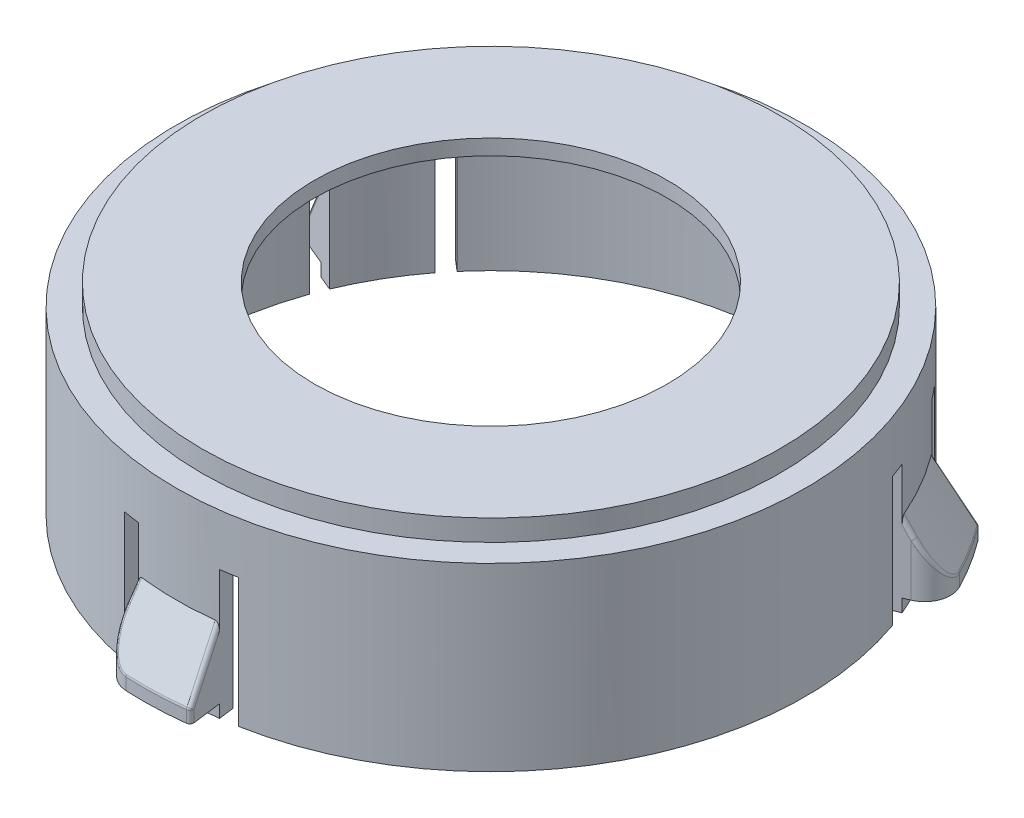
SolidWorks part; units mm, degrees
ref_plane "Front Plane" through (0, 0, 0) normal (0, 0, 1) x (1, 0, 0)
ref_plane "Top Plane" through (0, 0, 0) normal (0, 1, 0) x (1, 0, 0)
ref_plane "Right Plane" through (0, 0, 0) normal (1, 0, 0) x (0, 0, -1)
sketch "Sketch1" plane through (0, 0, 0) normal (0, 1, 0) x (1, 0, 0)
  circle A0 centre (0, 0) radius 24.5
  dimension "D1" = 49
extrude "Boss-Extrude1" add sketch "Sketch1" along normal blind 15.7
sketch "Sketch2" plane through (0, 15.7, 0) normal (0, 1, 0) x (1, 0, 0)
  circle A0 centre (0, 0) radius 22.5
  circle A1 centre (0, 0) radius 24.5 construction
  circle A2 centre (0, 0) radius 24.5
  dimension "D1" = 45
extrude "Cut-Extrude1" cut sketch "Sketch2" against normal blind 1.65
sketch "Sketch3" plane through (0, 15.7, 0) normal (0, 1, 0) x (1, 0, 0)
  circle A0 centre (0, 0) radius 13.75
  dimension "D1" = 27.5
shell "Shell1" thickness 1.2
extrude "Cut-Extrude2" cut sketch "Sketch3" against normal up to surface (1.2 mm away) up to face at (0, 14.5, 21.3)
sketch "Sketch4" plane through (0, 0, 0) normal (1, 0, 0) x (0, 0, -1)
  line L0 (-24.5, 6.5) -> (-24.5, 1)
  line L1 (-24.5, 14.05) -> (-24.5, 0) construction
  line L2 (-24.5, 14.05) -> (-24.5, 0) construction
  line L3 (-24.5, 1) -> (-27.1, 1)
  line L4 (-27.1, 1) -> (-27.1, 2)
  line L5 (-27.1, 2) -> (-24.5, 6.5)
  dimension "D1" = 2.6
  dimension "D2" = 1
  dimension "D3" = 5.5
  dimension "D4" = 1
ref_plane "Plane1" through (0, 1, 24.5) normal (0, -1, 0) x (-1, 0, 0)
sketch "Sketch5" plane through (0, 1, 24.5) normal (0, -1, 0) x (-1, 0, 0)
  line L0 (0, 0) -> (0, -8.4757) construction
  line L1 (0, 0) -> (0, -2.6) construction
  line L2 (0, -2.6) -> (-6.262, -2.6) construction
  line L3 (-3.5, -2.373) -> (-3.5, -2.6) construction
  line L4 (3.5, -2.373) -> (3.5, -2.6) construction
  circle A2 centre (0, 24.5) radius 27.1
  arc A3 (-3.5, -2.373) -> (3.5, -2.373) centre (0, 24.5) ccw
  point P15 (0, -2.6)
  dimension "D2" = 3.5
  dimension "D3" = 3.5
  dimension "D1" = 2.6
sweep "Sweep1" add profiles "Sketch4" path "Sketch5"
fillet "Fillet2" radius 2 1 edges at (-3.5, 1.5, 26.873)
fillet "Fillet3" radius 0.3 5 edges at (-3.1978, 6.0498, 24.5527) (1.0805, 2, 27.0784) (3.5, 1.5, 26.873) (3.3321, 4.25, 25.5839) (-2.2759, 2.3787, 26.7847)
sketch "Sketch7" plane through (0, 0, 0) normal (0, -1, 0) x (1, 0, 0)
  line L0 (3.461, 26.5739) -> (3.1642, 24.2948) construction
  line L1 (-3.2314, 24.8106) -> (-3.1642, 24.2948) construction
  line L2 (3.461, 26.5739) -> (3.1642, 24.2948) construction
  line L3 (-3.2314, 24.8106) -> (-3.1642, 24.2948) construction
  line L4 (0, 0) -> (7.9298, 43.1191) construction
  line L5 (0, 0) -> (-8.9475, 48.653) construction
  line L6 (-3.1642, 24.2948) -> (-3.0092, 23.1049)
  line L7 (-4.4314, 24.0959) -> (-4.2143, 22.9157)
  line L8 (3.1642, 24.2948) -> (3.0092, 23.1049)
  line L9 (4.4314, 24.0959) -> (4.2143, 22.9157)
  circle A0 centre (0, 0) radius 23.3 construction
  circle A1 centre (0, 0) radius 24.5 construction
  arc A2 (-3.0092, -23.1049) -> (3.0092, -23.1049) centre (0, 0) ccw
  arc A3 (-3.1642, -24.2948) -> (3.1642, -24.2948) centre (0, 0) ccw
  arc A4 (4.4314, 24.0959) -> (3.1642, 24.2948) centre (0, 0) ccw
  arc A5 (4.2143, 22.9157) -> (3.0092, 23.1049) centre (0, 0) ccw
  arc A6 (-3.0092, 23.1049) -> (-4.2143, 22.9157) centre (0, 0) ccw
  arc A7 (-3.1642, 24.2948) -> (-4.4314, 24.0959) centre (0, 0) ccw
  point P18 (4.4314, 24.0959)
  point P19 (4.2143, 22.9157)
  point P20 (-4.2143, 22.9157)
  point P21 (-4.4314, 24.0959)
  circle M5 centre (0, 0) radius 23.3
  circle M6 centre (0, 0) radius 24.5
  dimension "D1" = 3
  dimension "D2" = 3
extrude "Cut-Extrude3" cut sketch "Sketch7" against normal offset from surface (10.05 mm away) 4 contours L7 L6 M6 M5 | L9 L8 M6 M5 up to face at (0, 14.05, 22.5)
pattern_circular "CirPattern2" count 3 over 360 about axis through (0, 14.05, 0) along (0, 1, 0) of "Sweep1", "Fillet2", "Fillet3", "Cut-Extrude3"
